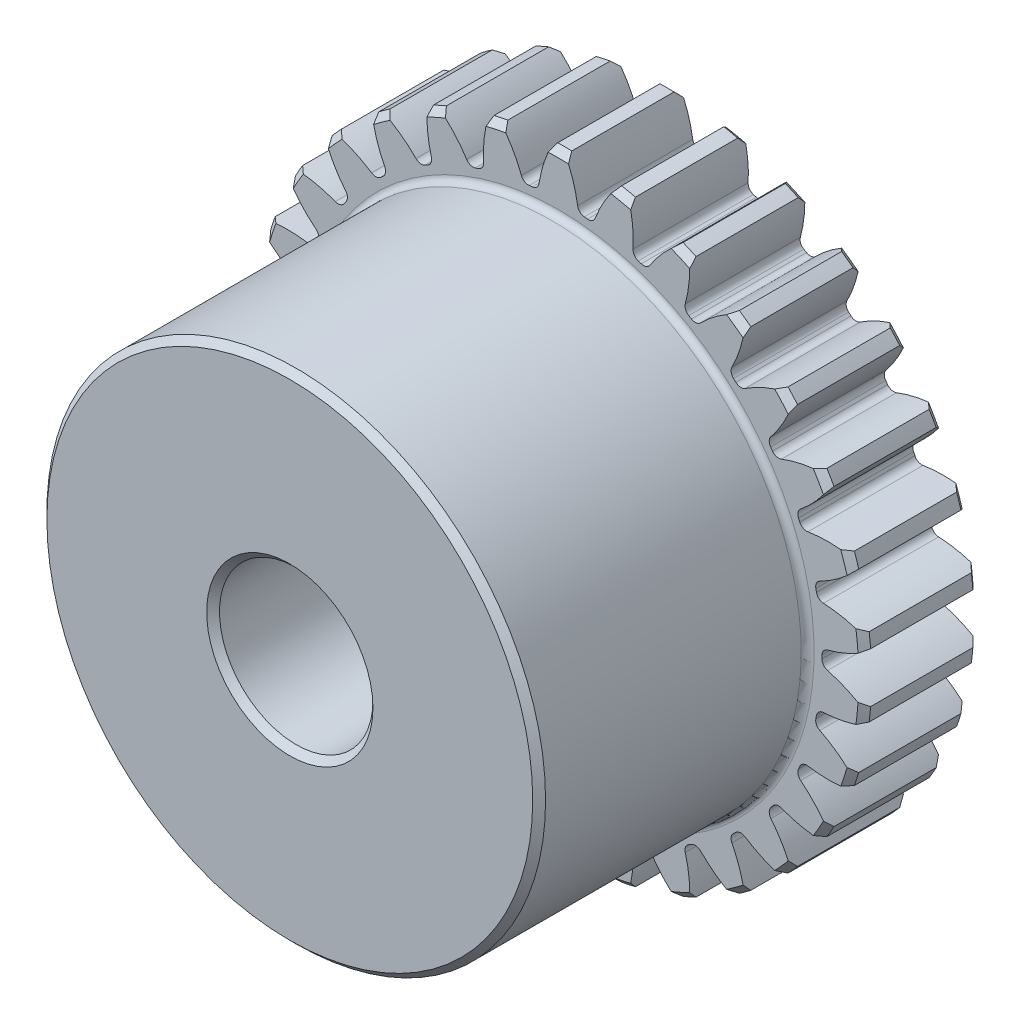
SolidWorks part; units mm, degrees
ref_plane "Front Plane" through (0, 0, 0) normal (0, 0, 1) x (1, 0, 0)
ref_plane "Top Plane" through (0, 0, 0) normal (0, 1, 0) x (1, 0, 0)
ref_plane "Right Plane" through (0, 0, 0) normal (1, 0, 0) x (0, 0, -1)
sketch "Sketch1" plane through (0, 0, 0) normal (0, 0, 1) x (1, 0, 0)
  line L0 (0, 0) -> (0, 7.5) construction
  line L1 (-2.4105, 8.3773) -> (2.4105, 6.6227) construction
  circle A0 centre (0, 0) radius 6.875 construction
  circle A1 centre (0, 0) radius 8 construction
  circle A2 centre (0, 0) radius 7.5 construction
  circle A3 centre (0, 0) radius 7.0477 construction
  circle A4 centre (0, 0) radius 6.5 construction
  circle A5 centre (0, 0) radius 2 construction
  point P8 (0.25, 0)
  point P13 (15, 0)
  dimension "OD" = 16
  dimension "Root Diameter" = 13.75
  dimension "Gear Pitch Diameter" = 15
  dimension "Base Diameter" = 14.0954
  dimension "Hub Diameter" = 13
  dimension "For Shaft Diameter" = 4
  dimension "Pressure Angle" = 20
  dimension "Number of Teeth" = 30
  dimension "Module" = 0.5
sketch "Sketch2" plane through (0, 0, 0) normal (1, 0, 0) x (0, 0, -1)
  line L0 (-7, 0) -> (3, 0) construction
  line L1 (3, 8) -> (3, -8) construction
  line L2 (0, -6.5) -> (-7, -6.5) construction
  line L3 (-7, 8) -> (3, 8) construction
  line L8 (-7, -6.5) -> (-7, 6.5) construction
  point P4 (0, 8)
  point P5 (-3.5, 0)
  dimension "Overall Width" = 10
  dimension "Hub Width" = 7
  dimension "Approx Set Screw Positon" = 3.5
  dimension "Face Width" = 3
sketch "Sketch3" plane through (0, 0, 0) normal (0, 0, 1) x (1, 0, 0)
  circle A0 centre (0, 0) radius 8
  circle A1 centre (0, 0) radius 8 construction
extrude "Boss-Extrude1" add sketch "Sketch3" against normal up to vertex (3 mm away) and the other way up to vertex (7 mm away) up to point (0, 0, -3) other way up to point (0, 0, 7)
sketch "Sketch5" plane through (0, 0, 0) normal (1, 0, 0) x (0, 0, -1)
  line L1 (0, 6.5) -> (-7, 6.5)
  line L2 (0, 6.5) -> (0, 8)
  line L3 (0, 8) -> (-7, 8)
  line L4 (-7, 6.5) -> (-7, 8)
  line L5 (-7, 0) -> (3, 0)
  line L6 (-7, 0) -> (-7, 2)
  line L7 (-7, 2) -> (3, 2)
  line L8 (3, 0) -> (3, 2)
  point P5 (0, 6.5)
  point P12 (0, 2)
revolve "Cut-Revolve1" cut sketch "Sketch5" angle 360 about L0
fillet "Fillet2" radius 0.1678 1 edges at (0, -6.5, 0)
chamfer "Chamfer1" distance 0.1678 angle 45 5 edges at (0, -2, -3) (0, -8, 0) (8, 0, -3) (0, -2, 7) (0, -6.5, 7)
sketch "Sketch4" plane through (0, 0, 0) normal (0, 0, 1) x (1, 0, 0)
  line L0 (6.8722, 0.1963) -> (6.8722, -0.1963)
  arc A3 (7.9733, 0.6527) -> (7.9733, -0.6527) centre (0, 0) cw
  circle A4 centre (0, 0) radius 8 construction
  arc A5 (6.8722, 0.1963) -> (7.9733, 0.6527) centre (6.1809, 3.4211) ccw
  circle A8 centre (0, 0) radius 6.875 construction
  arc A9 (6.8722, -0.1963) -> (7.9733, -0.6527) centre (6.1809, -3.4211) cw
  spline S0 degree 4 poles (7.0428, 0.2639) (7.0443, 0.264) (7.0485, 0.2642) (7.0564, 0.2649) (7.0694, 0.2664) (7.0858, 0.2686) (7.1071, 0.2721) (7.1321, 0.2767) (7.1595, 0.2826) (7.1893, 0.2896) (7.2189, 0.2973) (7.2484, 0.3055) (7.2777, 0.3143) (7.3131, 0.3255) (7.3555, 0.3399) (7.4048, 0.358) (7.4605, 0.38) (7.5171, 0.404) (7.5726, 0.429) (7.6283, 0.4558) (7.6821, 0.4828) (7.7377, 0.5123) (7.7888, 0.5404) (7.8458, 0.5736) (7.8917, 0.6009) (7.9518, 0.6387) (7.9872, 0.6616) (8.0285, 0.689) (8.0468, 0.7015) (8.0581, 0.7091) knots 0 0 0 0 0 0.005377 0.015084 0.028532 0.04661 0.064855 0.092111 0.119476 0.146842 0.174209 0.201575 0.228941 0.256307 0.307035 0.361767 0.4165 0.471232 0.525964 0.580697 0.635429 0.690161 0.744894 0.799626 0.854358 0.909091 0.954545 1 1 1 1 1 construction
  spline S1 degree 4 poles (7.0428, 0.2639) (7.0443, 0.264) (7.0485, 0.2642) (7.0564, 0.2649) (7.0694, 0.2664) (7.0858, 0.2686) (7.1071, 0.2721) (7.1321, 0.2767) (7.1595, 0.2826) (7.1893, 0.2896) (7.2189, 0.2973) (7.2484, 0.3055) (7.2777, 0.3143) (7.3131, 0.3255) (7.3555, 0.3399) (7.4048, 0.358) (7.4605, 0.38) (7.5171, 0.404) (7.5726, 0.429) (7.6283, 0.4558) (7.6821, 0.4828) (7.7377, 0.5123) (7.7888, 0.5404) (7.8458, 0.5736) (7.8917, 0.6009) (7.9388, 0.6305) (7.9617, 0.6451) (7.9733, 0.6527) knots 0 0 0 0 0 0.005377 0.015084 0.028532 0.04661 0.064855 0.092111 0.119476 0.146842 0.174209 0.201575 0.228941 0.256307 0.307035 0.361767 0.4165 0.471232 0.525964 0.580697 0.635429 0.690161 0.744894 0.799626 0.854358 0.909091 0.909091 0.909091 0.909091 0.909091 construction
  spline S2 degree 4 poles (7.0428, -0.2639) (7.0443, -0.264) (7.0485, -0.2642) (7.0564, -0.2649) (7.0694, -0.2664) (7.0858, -0.2686) (7.1071, -0.2721) (7.1321, -0.2767) (7.1595, -0.2826) (7.1893, -0.2896) (7.2189, -0.2973) (7.2484, -0.3055) (7.2777, -0.3143) (7.3131, -0.3255) (7.3555, -0.3399) (7.4048, -0.358) (7.4605, -0.38) (7.5171, -0.404) (7.5726, -0.429) (7.6283, -0.4558) (7.6821, -0.4828) (7.7377, -0.5123) (7.7888, -0.5404) (7.8458, -0.5736) (7.8917, -0.6009) (7.9518, -0.6387) (7.9872, -0.6616) (8.0285, -0.689) (8.0468, -0.7015) (8.0581, -0.7091) knots 0 0 0 0 0 0.005377 0.015084 0.028532 0.04661 0.064855 0.092111 0.119476 0.146842 0.174209 0.201575 0.228941 0.256307 0.307035 0.361767 0.4165 0.471232 0.525964 0.580697 0.635429 0.690161 0.744894 0.799626 0.854358 0.909091 0.954545 1 1 1 1 1 construction
  spline S3 degree 4 poles (7.0428, -0.2639) (7.0443, -0.264) (7.0485, -0.2642) (7.0564, -0.2649) (7.0694, -0.2664) (7.0858, -0.2686) (7.1071, -0.2721) (7.1321, -0.2767) (7.1595, -0.2826) (7.1893, -0.2896) (7.2189, -0.2973) (7.2484, -0.3055) (7.2777, -0.3143) (7.3131, -0.3255) (7.3555, -0.3399) (7.4048, -0.358) (7.4605, -0.38) (7.5171, -0.404) (7.5726, -0.429) (7.6283, -0.4558) (7.6821, -0.4828) (7.7377, -0.5123) (7.7888, -0.5404) (7.8458, -0.5736) (7.8917, -0.6009) (7.9388, -0.6305) (7.9617, -0.6451) (7.9733, -0.6527) knots 0 0 0 0 0 0.005377 0.015084 0.028532 0.04661 0.064855 0.092111 0.119476 0.146842 0.174209 0.201575 0.228941 0.256307 0.307035 0.361767 0.4165 0.471232 0.525964 0.580697 0.635429 0.690161 0.744894 0.799626 0.854358 0.909091 0.909091 0.909091 0.909091 0.909091 construction
  dimension "D1" = 0.3927
extrude "Cut-Extrude1" cut sketch "Sketch4" against normal through all both and the other way through all
fillet "Fillet1" radius 0.1963 2 edges at (6.8722, 0.1963, -1.5) (6.8722, -0.1963, -1.5)
pattern_circular "CirPattern1" count 30 over 360 about axis through (0, 0, 0) along (0, 0, 1) of "Cut-Extrude1", "Fillet1"
equation "\"Number of Teeth\"= 30"
equation "\"Module\"= 0.5"
equation "\"Diametral Pitch\"= 1 / \"Module\""
equation "\"Dedendum\"= 1.25 / \"Diametral Pitch\""
equation "\"Pitch Diameter\"= \"Module\" * \"Number of Teeth\""
equation "\"Root Diameter\"= \"Pitch Diameter\" - ( 2 * \"Dedendum\" )"
equation "\"Root Diameter@Sketch1\"=\"Root Diameter\""
equation "\"OD@Sketch1\" = \"Outside Diameter\""
equation "\"D1@CirPattern1\"=\"Number of Teeth\""
equation "\"Pressure Angle\"=20"
equation "\"Base Diameter\"= \"Pitch Diameter\" * cos ( \"Pressure Angle\" )"
equation "\"Outside Diameter\"= ( \"Number of Teeth\" + 2 ) / \"Diametral Pitch\""
equation "\"Pitch Angle\"= 360deg / \"Number of Teeth\""
equation "\"Alpha\"= sqr ( \"Pitch Diameter\" ^ 2 - \"Base Diameter\" ^ 2 ) / \"Base Diameter\" * 180 / PI - \"Pressure Angle\""
equation "\"Beta\"= ( \"Pitch Angle\" / 4 - \"Alpha\" )"
equation "\"Phi\"= sqr ( ( \"Outside Diameter\" / 2 ) ^ 2 - ( \"Base Diameter\" / 2 ) ^ 2 ) / ( \"Base Diameter\" / 2 )"
equation "\"Addendum\"= 1 / \"Diametral Pitch\""
equation "\"WorkingDepth\"= 2 / \"Diametral Pitch\""
equation "\"WholeDepth\"= 2.25 / \"Diametral Pitch\""
equation "\"Clearance\"= 0.25 / \"Diametral Pitch\""
equation "\"ToothThickness\"= ( pi * 2 ) / \"Diametral Pitch\""
equation "\"CircularPitch\"= pi / \"Diametral Pitch\""
equation "\"Number of Teeth@Sketch1\"=\"Number of Teeth\""
equation "\"Module@Sketch1\"=\"Module\""
equation "\"Pressure Angle@Sketch1\"=\"Pressure Angle\""
equation "\"Gear Pitch Diameter@Sketch1\"=\"Pitch Diameter\""
equation "\"Base Diameter@Sketch1\"=\"Base Diameter\""
equation "\"Fillet\"= \"Clearance\" * cos ( \"Pressure Angle\" ) * tan ( ( 90 + \"Pressure Angle\" ) / 2 )"
equation "\"D1@Fillet2\"=\"Fillet\""
equation "\"Approx Set Screw Positon@Sketch2\" = \"Hub Width@Sketch2\" / 2"
equation "\"D2\"= \"Fillet\" * 2"
equation "\"D1@Chamfer1\"=\"Fillet\""
equation "\"D1@Sketch4\"=\"CircularPitch\"*0.25"
equation "\"D1@Fillet1\"=\"CircularPitch\"*0.125"
